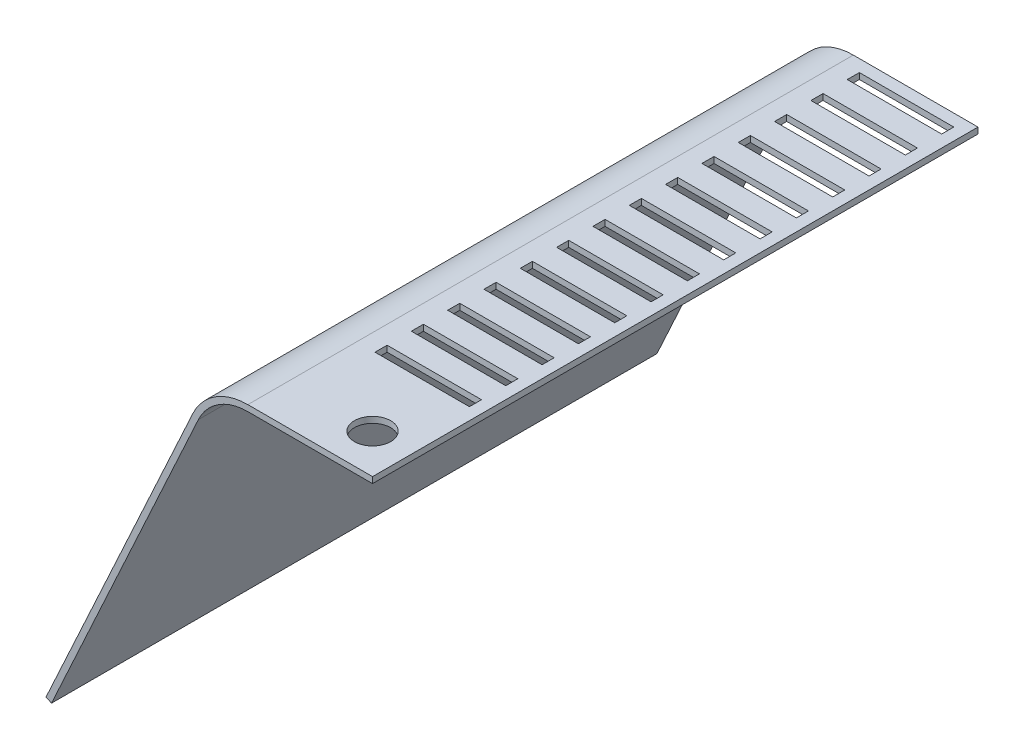
SolidWorks part; units mm, degrees
ref_plane "Front Plane" through (0, 0, 0) normal (0, 0, 1) x (1, 0, 0)
ref_plane "Top Plane" through (0, 0, 0) normal (0, 1, 0) x (1, 0, 0)
ref_plane "Right Plane" through (0, 0, 0) normal (1, 0, 0) x (0, 0, -1)
sketch "Sketch1" plane through (0, 0, 0) normal (0, 0, 1) x (1, 0, 0)
  line L0 (0, 0) -> (-205.95, 0)
  line L1 (-296.7862, -58.1816) -> (-539.333, -585.0317)
  arc A0 (-205.95, 0) -> (-296.7862, -58.1816) centre (-205.95, -100) ccw
  point P6 (-159.7314, -84.2631)
  point P7 (-54.9077, 0)
  dimension "D1" = 100
  dimension "D2" = 205.95
  dimension "D3" = 114.72
  dimension "D4" = 580
extrude "Extrude-Thin1" add sketch "Sketch1" along normal mid plane 1000 thin thin type one direction reverse wall 10
sketch "Sketch2" plane through (0, 0, 0) normal (0, 1, 0) x (1, 0, 0)
  line L0 (0, -500) -> (0, 500) construction
  line L1 (-175.95, 480) -> (-20, 480)
  line L2 (-175.95, 480) -> (-175.95, 460)
  line L3 (-175.95, 460) -> (-20, 460)
  line L4 (-20, 480) -> (-20, 460)
  line L5 (-175.95, 480) -> (-20, 460) construction
  line L6 (-175.95, 460) -> (-20, 480) construction
  line L7 (0, 500) -> (-205.95, 500) construction
  line L8 (-205.95, -500) -> (-205.95, 500) construction
  point P0 (-97.975, 470)
  dimension "D1" = 20
  dimension "D2" = 20
  dimension "D3" = 20
  dimension "D4" = 30
extrude "Cut-Extrude1" cut sketch "Sketch2" against normal through all
pattern_linear "LPattern1" count 14 spacing 60 along (0, 0, 1) of "Cut-Extrude1"
sketch "Sketch3" plane through (0, 0, 0) normal (0, 1, 0) x (1, 0, 0)
  line L0 (0, -500) -> (-205.95, -500) construction
  line L2 (0, -500) -> (0, 500) construction
  circle A0 centre (-65, -435) radius 30
  point P6 (0, -440.0568)
  dimension "D3" = 60
  dimension "D1" = 65
  dimension "D2" = 65
extrude "Cut-Extrude2" cut sketch "Sketch3" against normal through all
